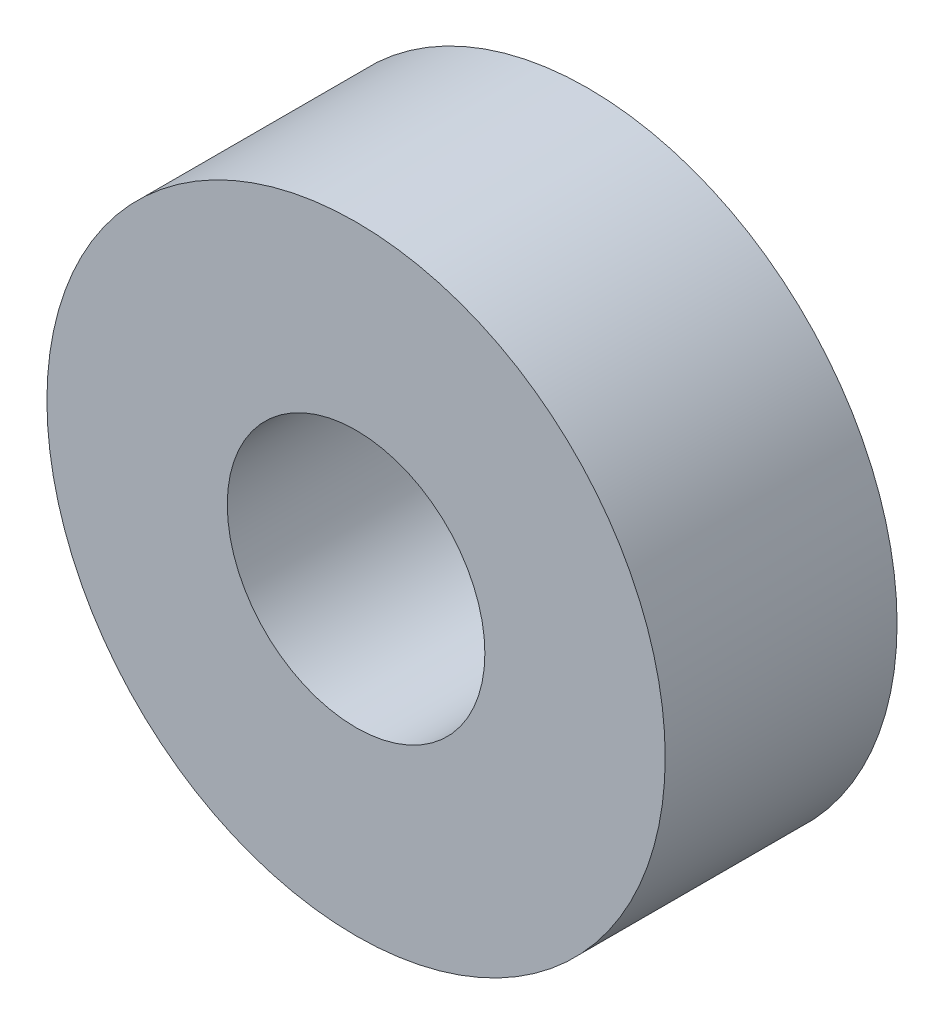
SolidWorks part; units mm, degrees
material "GCrl5A"
ref_plane "前视基准面" through (0, 0, 0) normal (0, 0, 1) x (1, 0, 0)
ref_plane "上视基准面" through (0, 0, 0) normal (0, 1, 0) x (1, 0, 0)
ref_plane "右视基准面" through (0, 0, 0) normal (1, 0, 0) x (0, 0, -1)
sketch "草图1" plane through (0, 0, 0) normal (0, 0, 1) x (1, 0, 0)
  circle A0 centre (0, 0) radius 12
  circle A1 centre (0, 0) radius 5
  dimension "D1" = 10
  dimension "D2" = 24
extrude "凸台-拉伸1" add sketch "草图1" along normal blind 9
